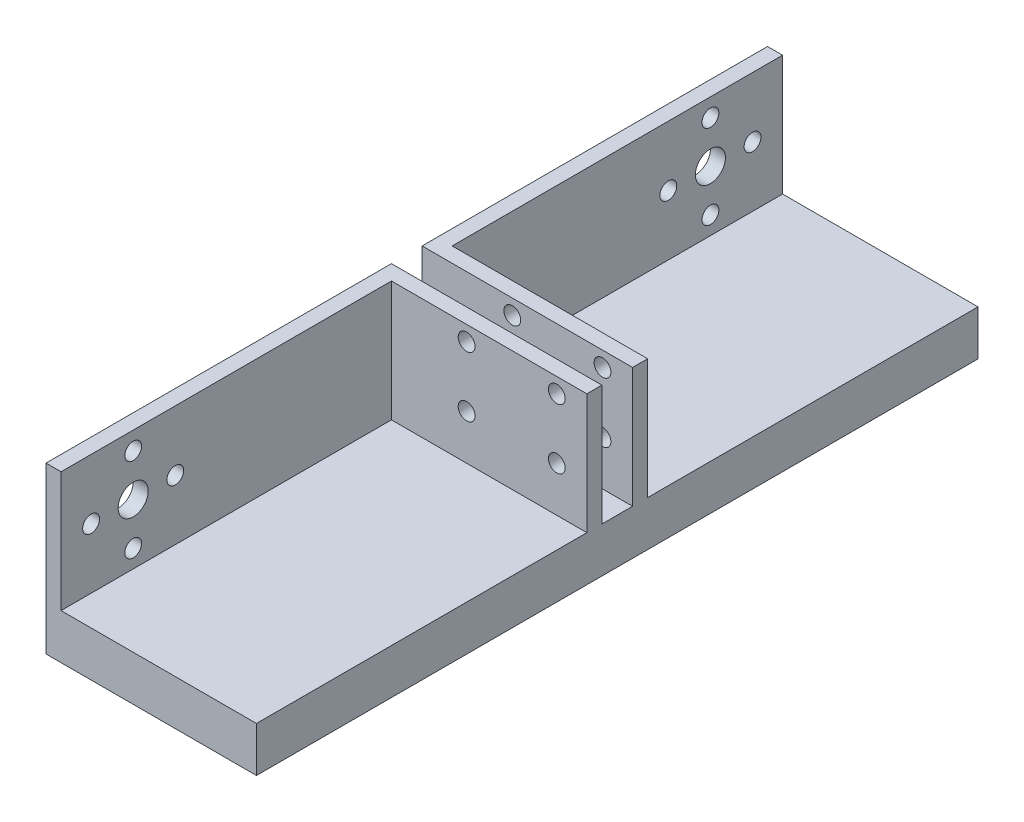
SolidWorks part; units mm, degrees
ref_plane "Front Plane" through (0, 0, 0) normal (0, 0, 1) x (1, 0, 0)
ref_plane "Top Plane" through (0, 0, 0) normal (0, 1, 0) x (1, 0, 0)
ref_plane "Right Plane" through (0, 0, 0) normal (1, 0, 0) x (0, 0, -1)
sketch "Sketch1" plane through (0, 0, 0) normal (0, 1, 0) x (1, 0, 0)
  line L1 (-35, 60) -> (0, 60)
  line L2 (-35, 60) -> (-35, -60)
  line L3 (-35, -60) -> (0, -60)
  line L4 (0, 60) -> (0, -60)
  point P4 (0, 0)
  dimension "D1" = 35
  dimension "D2" = 120
extrude "Boss-Extrude1" add sketch "Sketch1" along normal blind 7.5
sketch "Sketch2" plane through (0, 7.5, 0) normal (0, 1, 0) x (1, 0, 0)
  line L5 (0, -60) -> (0, 60) construction
  line L6 (-32.5, 5.05) -> (0, 5.05)
  line L7 (-32.5, 5.05) -> (-32.5, 2.55)
  line L8 (-32.5, 2.55) -> (0, 2.55)
  line L9 (0, 5.05) -> (0, 2.55)
  line L10 (-16.25, 2.55) -> (-16.25, -2.55) construction
  line L11 (0, -2.55) -> (-32.5, -2.55)
  line L12 (0, -2.55) -> (0, -5.05)
  line L13 (0, -5.05) -> (-32.5, -5.05)
  line L14 (-32.5, -2.55) -> (-32.5, -5.05)
  line L16 (-32.5, 2.55) -> (-35, 2.55)
  line L17 (-32.5, 2.55) -> (-32.5, 60)
  line L18 (-32.5, 60) -> (-35, 60)
  line L19 (-35, 2.55) -> (-35, 60)
  line L20 (-32.5, -2.55) -> (-35, -2.55)
  line L21 (-32.5, -2.55) -> (-32.5, -60)
  line L22 (-32.5, -60) -> (-35, -60)
  line L23 (-35, -2.55) -> (-35, -60)
  point P21 (-16.25, 0)
  line M6 (-35, 60) -> (-35, -60)
  line M7 (-35, -60) -> (0, -60)
  line M8 (0, -60) -> (0, 60)
  line M9 (0, 60) -> (-35, 60)
  dimension "D1" = 2.5
  dimension "D2" = 2.5
  dimension "D3" = 5.1
extrude "Boss-Extrude2" add sketch "Sketch2" along normal blind 20 contours L7 L8 L6 M8 | L7 L17 L16 M9 M6 | L11 L14 L13 M8 | L21 L14 L20 M6 M7
sketch "Sketch4" plane through (0, 0, 5.05) normal (0, 0, 1) x (1, 0, 0)
  line L0 (-5, 25) -> (-5, 15) construction
  line L1 (-5, 15) -> (-20, 15) construction
  line L2 (-20, 15) -> (-20, 25) construction
  line L3 (-20, 25) -> (-5, 25) construction
  line L4 (0, 27.5) -> (0, 7.5) construction
  line L5 (0, 27.5) -> (-32.5, 27.5) construction
  circle A0 centre (-5, 25) radius 1.4
  circle A1 centre (-20, 25) radius 1.4
  circle A2 centre (-5, 15) radius 1.4
  circle A3 centre (-20, 15) radius 1.4
  dimension "D1" = 2.8
  dimension "D2" = 15
  dimension "D3" = 10
  dimension "D4" = 5
  dimension "D5" = 2.5
extrude "Cut-Extrude2" cut sketch "Sketch4" against normal blind 12
sketch "Sketch5" plane through (-32.5, 0, 0) normal (1, 0, 0) x (0, 0, -1)
  line L0 (-55, 17.5) -> (-48, 17.5) construction
  line L1 (-48, 17.5) -> (-48, 24.5) construction
  line L2 (-60, 27.5) -> (-60, 7.5) construction
  line L3 (0, 33.9733) -> (0, -3.7037) construction
  line L4 (48, 17.5) -> (48, 24.5) construction
  line L5 (55, 17.5) -> (48, 17.5) construction
  line L6 (-5.05, 27.5) -> (-60, 27.5) construction
  circle A0 centre (-48, 17.5) radius 2.5
  circle A1 centre (-48, 24.5) radius 1.4
  circle A2 centre (-55, 17.5) radius 1.4
  circle A3 centre (-48, 10.5) radius 1.4
  circle A4 centre (-41, 17.5) radius 1.4
  circle A5 centre (41, 17.5) radius 1.4
  circle A6 centre (48, 10.5) radius 1.4
  circle A7 centre (55, 17.5) radius 1.4
  circle A8 centre (48, 24.5) radius 1.4
  circle A9 centre (48, 17.5) radius 2.5
  dimension "D1" = 5
  dimension "D2" = 2.8
  dimension "D3" = 12
  dimension "D4" = 7
  dimension "D5" = 10
extrude "Cut-Extrude3" cut sketch "Sketch5" against normal blind 2.5
